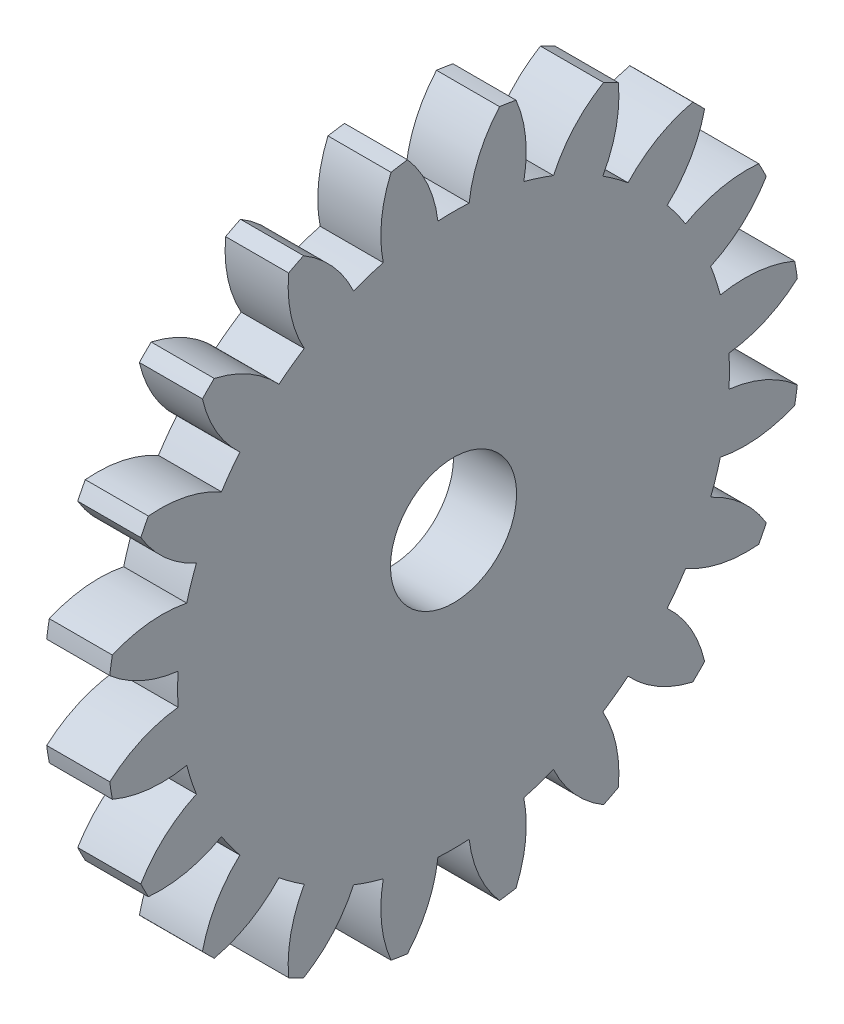
SolidWorks part; units mm, degrees
ref_plane "Plane1" through (0, 0, 0) normal (0, 0, 1) x (1, 0, 0)
ref_plane "Plane2" through (0, 0, 0) normal (0, 1, 0) x (1, 0, 0)
ref_plane "Plane3" through (0, 0, 0) normal (1, 0, 0) x (0, 0, -1)
sketch "HoldingSke" plane through (0, 0, 0) normal (0, 1, 0) x (1, 0, 0)
  line L0 (0, 0) -> (0.3759, -0.1368)
  line L1 (-15, 0) -> (100, 0) construction
  line L2 (0, 0) -> (-2.1039, 2.3779)
  line L3 (0, 0) -> (-11.863, 4.5341)
  line L4 (0, 0) -> (8.1152, 2.9537)
  line L5 (0, 0) -> (-46.8476, -17.4728)
  line L6 (0, 0) -> (-4.1448, -2.7965)
  line L7 (-2.1039, 2.3779) -> (8.6586, 51.2059)
  line L8 (-76.2, 54.61) -> (-74.4, 54.61)
  line L9 (-71.009, 38.7566) -> (-53.1078, 45.2721)
  line L10 (-76.2, 71.12) -> (104.1128, 71.12)
  line L11 (0, 0) -> (-5, 0)
  line L12 (-76.2, 101.6) -> (-76.113, 101.6)
  line L13 (24.9733, 27.94) -> (52.9518, 28.4284)
  line L14 (24.9733, 27.94) -> (24.9743, 27.94)
  line L15 (24.9733, 27.94) -> (100.4006, 29.5858)
  line L16 (-63.627, -2.5) -> (-12.827, -2.5)
  circle A0 centre (0, 0) radius 5
  circle A1 centre (0, 0) radius 21.874
  circle A2 centre (0, 0) radius 37.5
  circle A3 centre (0, 0) radius 5
  dimension "MHD" = 43.748
  dimension "Hub_dia" = 75
  dimension "Bore" = 10
  dimension "MBD" = 10
  dimension "Num_teeth" = 20
  dimension "Pitch" = 0.4
  dimension "Overall_len" = 50
  dimension "Show_teeth" = 20
  dimension "Thickness" = 5
  dimension "OAL" = 50.0001
  dimension "T_dim" = 1.8
  dimension "Ap" = 20
  dimension "H" = 19.05
  dimension "Pitch_radius" = 180.3128
  dimension "Width" = 5
  dimension "Backlash" = 0.087
  dimension "Addendum_fac" = 1
  dimension "Dedendum_fac" = 1.25
  dimension "Clearance_fac" = 0.25
  dimension "Dedendum_add" = 0.001
  dimension "Module" = 2.5
sketch "BasProSke" plane through (0, 0, 0) normal (0, 1, 0) x (1, 0, 0)
  line L0 (-10, 0) -> (60, 0) construction
  line L1 (0, 0) -> (0, 27.5)
  line L2 (0, 0) -> (5, 0)
  line L3 (5, 0) -> (5, 27.5)
  line L4 (5, 27.5) -> (0, 27.5)
  dimension "Thickness" = 5
  dimension "Diameter" = 55
revolve "Base-Revolve" add sketch "BasProSke" angle 360 about L0
sketch "TooCutSke" plane through (0, 0, 0) normal (1, 0, 0) x (0, 0, -1)
  line L1 (0, 0) -> (0, 107) construction
  line L2 (0, 0) -> (-2.1137, 24.9105) construction
  line L3 (0, 0) -> (-7.8012, 49.2549) construction
  line L4 (-2.1137, 24.9105) -> (-3.9006, 24.6275) construction
  arc A0 (1.2377, 21.839) -> (-1.2377, 21.839) centre (0, 0) ccw
  arc A1 (3.6672, 27.28) -> (-3.6672, 27.28) centre (0, 0) ccw
  circle A2 centre (0, 0) radius 25 construction
  circle A3 centre (0, 0) radius 23.4923 construction
  arc A4 (-1.2377, 21.839) -> (-3.6672, 27.28) centre (-11.1689, 20.6675) ccw
  arc A5 (3.6672, 27.28) -> (1.2377, 21.839) centre (11.1689, 20.6675) ccw
  dimension "Root_dia" = 43.748
  dimension "Overcut_dia" = 55.0508
  dimension "Pitch_dia" = 50
  dimension "Base_dia" = 46.9846
  dimension "Flank_rad" = 10
  dimension "Half_ang" = 9
  dimension "Half_CT" = 1.8092
extrude "ToothCut" cut sketch "TooCutSke" along normal through all
fillet "Breaks" [suppressed] radius 0.05
fillet "RootFillets" [suppressed] radius 0.626
pattern_circular "TeethCuts" count 20 every 18 about axis through (-10, 0, 0) along (1, 0, 0) of "ToothCut", "RootFillets", "Breaks"
sketch "HubNeaOneSke" plane through (0, 0, 0) normal (-1, 0, 0) x (0, 0, 1)
  circle A0 centre (0, 0) radius 21.874
  dimension "Diameter" = 43.748
extrude "HubNearOne" [suppressed] add sketch "HubNeaOneSke" along normal blind 45.0001
sketch "HubNeaBotSke" plane through (0, 0, 0) normal (-1, 0, 0) x (0, 0, 1)
  circle A0 centre (0, 0) radius 21.874
  dimension "Diameter" = 43.748
extrude "HubNearBoth" [suppressed] add sketch "HubNeaBotSke" along normal blind 22.5
ref_plane "FarPln" through (5, 0, 0) normal (1, 0, 0) x (0, 0, -1)
sketch "HubFarSke" plane through (5, 0, 0) normal (1, 0, 0) x (0, 0, -1)
  circle A0 centre (0, 0) radius 21.874
  dimension "Diameter" = 43.748
extrude "HubFar" [suppressed] add sketch "HubFarSke" along normal blind 22.5
sketch "BorSke" plane through (0, 0, 0) normal (1, 0, 0) x (0, 0, -1)
  circle A0 centre (0, 0) radius 5
  dimension "Diameter" = 10
extrude "Bore" cut sketch "BorSke" along normal mid plane 100.0001
sketch "KeySke" plane through (0, 0, 0) normal (1, 0, 0) x (0, 0, -1)
  line L0 (-2, 0) -> (-2, 6.8)
  line L1 (-2, 6.8) -> (2, 6.8)
  line L2 (2, 6.8) -> (2, 0)
  line L3 (0, 0) -> (0, 34) construction
  line L4 (-2, 0) -> (2, 0)
  dimension "Offset" = 6.8
  dimension "Width" = 4
extrude "Keyway" [suppressed] cut sketch "KeySke" along normal mid plane 100.0001
pattern_circular "Keyway2" [suppressed] count 2 every 90 about axis through (-10, 0, 0) along (1, 0, 0)
equation "' \"Module@HoldingSke\" = 6.35"
equation "' \"Num_teeth@HoldingSke\" = 12"
equation "' \"Ap@HoldingSke\" =  20"
equation "' \"Ap@HoldingSke\" = 20"
equation "' \"Width@HoldingSke\" = 0.5 * 25.4"
equation "' \"Hub_dia@HoldingSke\"= 1 * 25.4"
equation "' \"Hub_dia@HoldingSke\" = 1 * 25.4"
equation "' \"Overall_len@HoldingSke\" = 1.0 * 25.4"
equation "' \"Bore@HoldingSke\" = 0.75 * 25.4"
equation "' \"T_dim@HoldingSke\" = 0.1 * 25.4"
equation "' \"Width@KeySke\" = 0.25 * 25.4"
equation "' \"Show_teeth@HoldingSke\" = 13"
equation "' \"Backlash@HoldingSke\" = 0.009 * 25.4"
equation "' \"Addendum_fac@HoldingSke\" = 1.0"
equation "' \"Dedendum_fac@HoldingSke\" = 1.25"
equation "' \"Dedendum_add@HoldingSke\" = 0.00005 * 25.4"
equation "' \"Clearance_fac@HoldingSke\" = 0.25"
equation "\"Pitch@HoldingSke\" = 1 / \"Module@HoldingSke\""
equation "\"Overcut_dia@TooCutSke\" = (\"Num_teeth@HoldingSke\" + 2 * \"Addendum_fac@HoldingSke\") / \"Pitch@HoldingSke\" + 0.002 * 25.4"
equation "\"Pitch_dia@TooCutSke\" = \"Num_teeth@HoldingSke\" / \"Pitch@HoldingSke\""
equation "\"Base_dia@TooCutSke\" = \"Num_teeth@HoldingSke\" / \"Pitch@HoldingSke\" * cos((\"Ap@HoldingSke\"  * 3.14159265 / 180))"
equation "\"Root_dia@TooCutSke\" = (\"Num_teeth@HoldingSke\" + 2) / \"Pitch@HoldingSke\" - 2 * (\"Addendum_fac@HoldingSke\" + \"Dedendum_fac@HoldingSke\") / \"Pitch@HoldingSke\" - \"Dedendum_add@HoldingSke\" * 2"
equation "\"Half_ang@TooCutSke\" = 180 / \"Num_teeth@HoldingSke\""
equation "\"Half_CT@TooCutSke\" = \"Num_teeth@HoldingSke\" / \"Pitch@HoldingSke\" * sin((3.14159265 / 2 / \"Num_teeth@HoldingSke\")) / 2 - 7 * \"Backlash@HoldingSke\" / 4"
equation "\"Flank_rad@TooCutSke\" = \"Num_teeth@HoldingSke\" / \"Pitch@HoldingSke\" / 5"
equation "\"Radius@RootFillets\" = \"Clearance_fac@HoldingSke\" / \"Pitch@HoldingSke\" + \"Dedendum_add@HoldingSke\""
equation "\"Break_rad@Breaks\" = 0.02 / \"Pitch@HoldingSke\""
equation "\"Thickness@HoldingSke\" = \"Width@HoldingSke\""
equation "\"OAL@HoldingSke\" = \"Thickness@HoldingSke\""
equation "\"MHD@HoldingSke\" = (\"Num_teeth@HoldingSke\" + 2) / \"Pitch@HoldingSke\" - 2 * (\"Addendum_fac@HoldingSke\" + \"Dedendum_fac@HoldingSke\")  / \"Pitch@HoldingSke\" - \"Dedendum_add@HoldingSke\" * 2"
equation "\"MBD@HoldingSke\" = (\"Num_teeth@HoldingSke\" + 2) / \"Pitch@HoldingSke\" - 2 * (\"Addendum_fac@HoldingSke\" + \"Dedendum_fac@HoldingSke\")  / \"Pitch@HoldingSke\" - \"Dedendum_add@HoldingSke\" * 2 - 0.002 * 25.4"
equation "\"MHD@HoldingSke\" = ((sgn( \"MHD@HoldingSke\" - \"Hub_dia@HoldingSke\" )-1)*( \"MHD@HoldingSke\" - \"Hub_dia@HoldingSke\" ))/-2+ \"Hub_dia@HoldingSke\""
equation "\"MBD@HoldingSke\" = ((sgn( \"MBD@HoldingSke\" - \"Bore@HoldingSke\" )-1)*( \"MBD@HoldingSke\" - \"Bore@HoldingSke\" ))/-2+ \"Bore@HoldingSke\""
equation "\"OAL@HoldingSke\" = ((sgn( \"OAL@HoldingSke\" - \"Overall_len@HoldingSke\" )+1)*( \"OAL@HoldingSke\" - \"Overall_len@HoldingSke\" ))/2 + \"Overall_len@HoldingSke\" + 0.000002 * 25.4"
equation "\"Num_teeth@TeethCuts\" = int( \"Show_teeth@HoldingSke\" ) + 1"
equation "\"Num_teeth@TeethCuts\" = ((sgn( \"Num_teeth@TeethCuts\" - \"Num_teeth@HoldingSke\" )-1)*( \"Num_teeth@TeethCuts\" - \"Num_teeth@HoldingSke\" ))/-2+ \"Num_teeth@HoldingSke\""
equation "\"Num_teeth@TeethCuts\" = ((sgn( \"Num_teeth@TeethCuts\" - 2.0)+1)*( \"Num_teeth@TeethCuts\" - 2.0))/2 +2.0"
equation "\"Angle@TeethCuts\" = 360.0 / \"Num_teeth@HoldingSke\""
equation "\"Diameter@BasProSke\" = (\"Num_teeth@HoldingSke\" + 2 * \"Addendum_fac@HoldingSke\") / \"Pitch@HoldingSke\""
equation "\"Thickness@BasProSke\"  = \"Thickness@HoldingSke\""
equation "' \"Fillet_rad@BasProSke\" =  \"Thickness@HoldingSke\" * 0.05"
equation "' \"Fillet_rad@BasProSke\" = \"Thickness@HoldingSke\" * 0.05"
equation "\"MHD@HoldingSke\" = ((sgn( \"MHD@HoldingSke\" - \"Root_dia@TooCutSke\" )-1)*( \"MHD@HoldingSke\" - \"Root_dia@TooCutSke\" ))/-2+ \"Root_dia@TooCutSke\""
equation "\"Diameter@HubNeaOneSke\" = \"MHD@HoldingSke\""
equation "\"Length@HubNearOne\" = \"OAL@HoldingSke\" - \"Thickness@BasProSke\""
equation "\"Diameter@HubNeaBotSke\" = \"MHD@HoldingSke\""
equation "\"Length@HubNearBoth\" = ( \"OAL@HoldingSke\" - \"Thickness@BasProSke\" ) / 2.0"
equation "\"Thickness@FarPln\" = \"Thickness@BasProSke\""
equation "\"Diameter@HubFarSke\" = \"MHD@HoldingSke\""
equation "\"Length@HubFar\" = ( \"OAL@HoldingSke\" - \"Thickness@BasProSke\" ) / 2.0"
equation "\"Diameter@BorSke\" = \"MBD@HoldingSke\""
equation "\"D1@Bore\" = \"OAL@HoldingSke\" * 2.0"
equation "\"D1@Keyway\" = \"OAL@HoldingSke\" * 2.0"
equation "\"Offset@KeySke\" = \"T_dim@HoldingSke\" + \"MBD@HoldingSke\" / 2.0"
